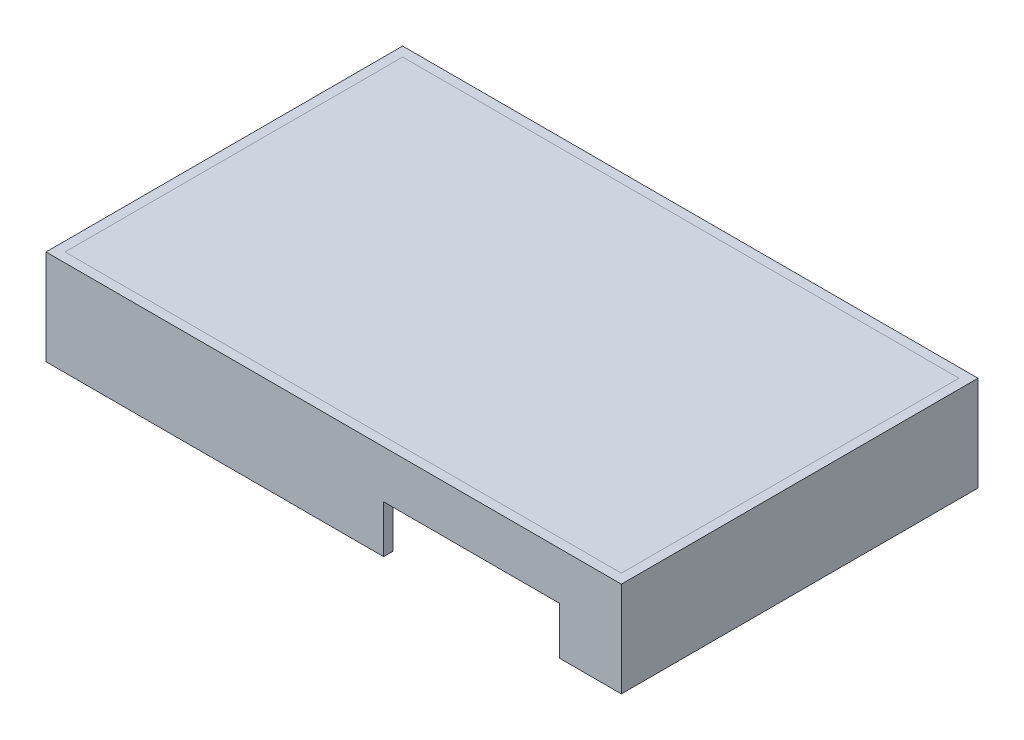
SolidWorks part; units mm, degrees
ref_plane "Front Plane" through (0, 0, 0) normal (0, 0, 1) x (1, 0, 0)
ref_plane "Top Plane" through (0, 0, 0) normal (0, 1, 0) x (1, 0, 0)
ref_plane "Right Plane" through (0, 0, 0) normal (1, 0, 0) x (0, 0, -1)
sketch "Sketch1" plane through (0, 0, 0) normal (0, 1, 0) x (1, 0, 0)
  line L1 (-58.5, -35.5) -> (58.5, -35.5)
  line L2 (-58.5, -35.5) -> (-58.5, 35.5)
  line L3 (-58.5, 35.5) -> (58.5, 35.5)
  line L4 (58.5, -35.5) -> (58.5, 35.5)
  line L5 (-58.5, -35.5) -> (58.5, 35.5) construction
  line L6 (-58.5, 35.5) -> (58.5, -35.5) construction
  point P0 (0, 0)
  dimension "D1" = 117
  dimension "D2" = 71
extrude "TopShield" add sketch "Sketch1" along normal blind 1.5875
sketch "Sketch4" plane through (0, 1.5875, 0) normal (0, 1, 0) x (1, 0, 0)
  line L0 (60.5, -37.5) -> (60.5, 37.5)
  line L1 (60.5, 37.5) -> (-60.5, 37.5)
  line L2 (-60.5, 37.5) -> (-60.5, -37.5)
  line L3 (-60.5, -37.5) -> (60.5, -37.5)
  line L4 (58.5, -35.5) -> (58.5, 35.5)
  line L5 (58.5, 35.5) -> (-58.5, 35.5)
  line L6 (-58.5, 35.5) -> (-58.5, -35.5)
  line L7 (-58.5, -35.5) -> (58.5, -35.5)
  line L8 (58.5, -35.5) -> (58.5, 35.5)
  line L9 (58.5, 35.5) -> (-58.5, 35.5)
  line L10 (-58.5, 35.5) -> (-58.5, -35.5)
  line L11 (-58.5, -35.5) -> (58.5, -35.5)
  dimension "D1" = 0
  dimension "D2" = 2
extrude "Walls" add sketch "Sketch4" against normal blind 20 separate body
sketch "Sketch5" plane through (0, -18.4125, 0) normal (0, -1, 0) x (1, 0, 0)
  line L0 (0, -55) -> (0, 55) construction
  line L1 (-58.5, 35.5) -> (-48.5, 35.5)
  line L2 (-58.5, 35.5) -> (-58.5, 25.5)
  line L3 (-58.5, 25.5) -> (-48.5, 25.5)
  line L4 (-48.5, 35.5) -> (-48.5, 25.5)
  line L5 (48.5, 35.5) -> (48.5, 25.5)
  line L6 (58.5, 25.5) -> (48.5, 25.5)
  line L7 (58.5, 35.5) -> (58.5, 25.5)
  line L8 (58.5, 35.5) -> (48.5, 35.5)
  line L9 (55, 0) -> (-55, 0) construction
  line L10 (58.5, -35.5) -> (48.5, -35.5)
  line L11 (58.5, -35.5) -> (58.5, -25.5)
  line L12 (58.5, -25.5) -> (48.5, -25.5)
  line L13 (48.5, -35.5) -> (48.5, -25.5)
  line L14 (-48.5, -35.5) -> (-48.5, -25.5)
  line L15 (-58.5, -25.5) -> (-48.5, -25.5)
  line L16 (-58.5, -35.5) -> (-58.5, -25.5)
  line L17 (-58.5, -35.5) -> (-48.5, -35.5)
  dimension "D1" = 10
extrude "Mounts" add sketch "Sketch5" against normal blind 3
hole_wizard "#4-40 Tapped Hole1" positions "Sketch2" profile "Sketch3" tap size "#4-40" standard "ANSI Inch" end condition up to next
sketch "Sketch2" plane through (0, -18.4125, 0) normal (0, 1, 0) x (1, 0, 0)
  line L0 (58.5, 35.5) -> (-58.5, 35.5) construction
  line L1 (-58.5, 35.5) -> (-58.5, -35.5) construction
  line L2 (0, -55) -> (0, 55) construction
  line L3 (-55, 0) -> (55, 0) construction
  point P0 (-53.5, 30.5)
  point P9 (53.5, 30.5)
  point P12 (53.5, -30.5)
  point P13 (-53.5, -30.5)
  dimension "D1" = 5
  dimension "D2" = 5
sketch "Sketch3" plane through (-53.5, -18.4125, -30.5) normal (1, 0, 0) x (0, 0, -1)
  line L0 (0, 0) -> (0, 20)
  line L1 (0, 20) -> (1.1303, 20)
  line L2 (1.1303, 20) -> (1.1303, 0)
  line L5 (1.1303, 0) -> (0, 0)
  line L11 (0, -6.35) -> (0, 107.95) construction
  dimension "Thru Tap Drill Dia." = 2.2606
  dimension "Thru Tap Drill Depth" = 20
sketch "Sketch6" plane through (0, 0, -37.5) normal (0, 0, -1) x (-1, 0, 0)
  line L0 (-60.5, -18.4125) -> (60.5, -18.4125) construction
  line L1 (50.5, -18.4125) -> (35.5, -18.4125)
  line L2 (50.5, -18.4125) -> (50.5, -6.4125)
  line L3 (50.5, -6.4125) -> (35.5, -6.4125)
  line L4 (35.5, -18.4125) -> (35.5, -6.4125)
  line L5 (60.5, -18.4125) -> (60.5, 1.5875) construction
  line L7 (17.5, -18.4125) -> (3.5, -18.4125)
  line L8 (17.5, -18.4125) -> (17.5, -9.1246)
  line L9 (17.5, -9.1246) -> (3.5, -9.1246)
  line L10 (3.5, -18.4125) -> (3.5, -9.1246)
  dimension "D1" = 10
  dimension "D2" = 25
  dimension "D3" = 12
  dimension "D4" = 43
  dimension "D5" = 57
extrude "PowerAndMotor" cut sketch "Sketch6" against normal up to next
sketch "Sketch7" plane through (0, 0, 37.5) normal (0, 0, 1) x (1, 0, 0)
  line L0 (-60.5, -18.4125) -> (60.5, -18.4125) construction
  line L5 (47.5, -18.4125) -> (10.5, -18.4125)
  line L6 (47.5, -18.4125) -> (47.5, -8.4125)
  line L7 (47.5, -8.4125) -> (10.5, -8.4125)
  line L8 (10.5, -18.4125) -> (10.5, -8.4125)
  line L9 (60.5, -18.4125) -> (60.5, 1.5875) construction
  dimension "D1" = 13
  dimension "D2" = 50
  dimension "D3" = 10
extrude "Controls" cut sketch "Sketch7" against normal up to next (2 mm away)
equation "\"PCB_Length\"= 117"
equation "\"D1@Sketch1\"=\"PCB_Length\""
equation "\"PCB_Width\"=71"
equation "\"D2@Sketch1\"=\"PCB_Width\""
equation "\"ShieldHeight\"=20"
equation "\"D1@Walls\" = \"ShieldHeight\""
